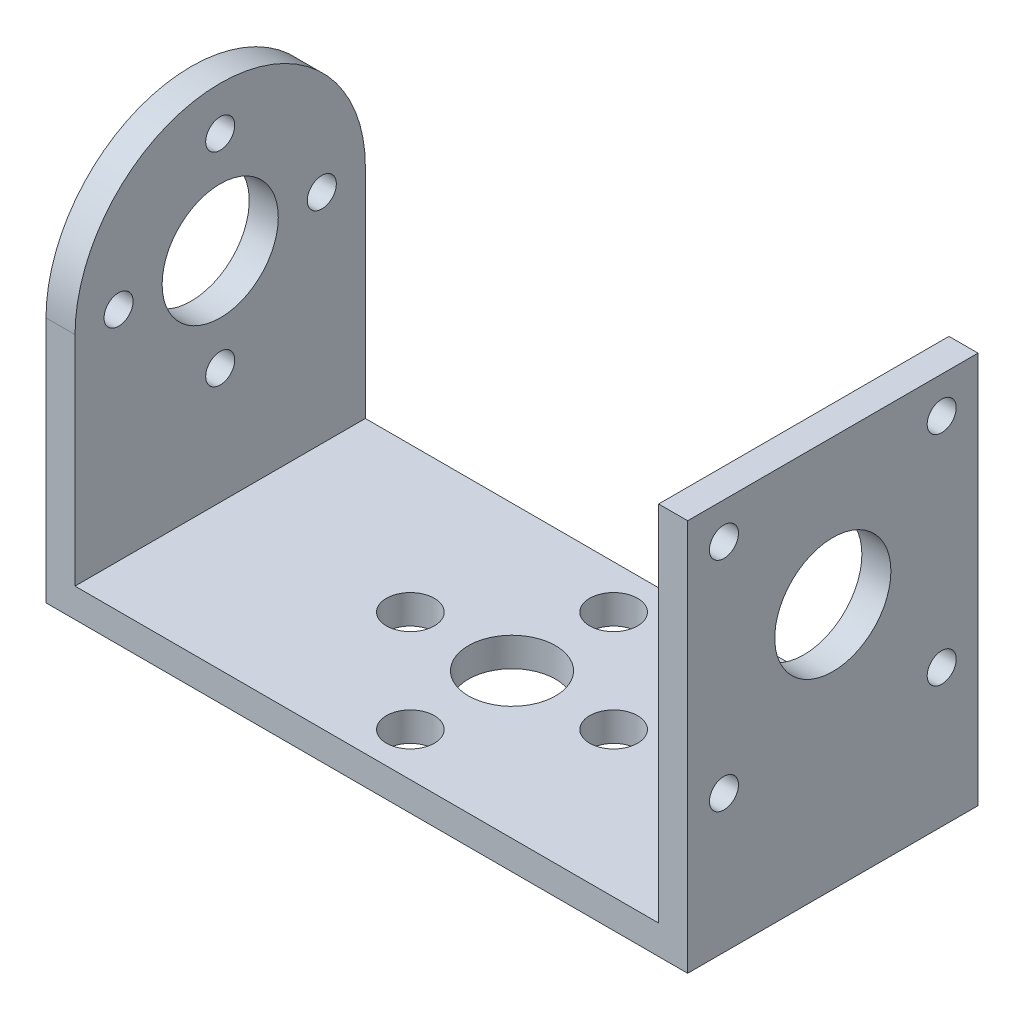
SolidWorks part; units mm, degrees
ref_plane "前视基准面" through (0, 0, 0) normal (0, 0, 1) x (1, 0, 0)
ref_plane "上视基准面" through (0, 0, 0) normal (0, 1, 0) x (1, 0, 0)
ref_plane "右视基准面" through (0, 0, 0) normal (1, 0, 0) x (0, 0, -1)
sketch "草图1" plane through (0, 0, 0) normal (0, 1, 0) x (1, 0, 0)
  line L1 (-22.1, -10) -> (22.1, -10)
  line L2 (-22.1, -10) -> (-22.1, 10)
  line L3 (-22.1, 10) -> (22.1, 10)
  line L4 (22.1, -10) -> (22.1, 10)
  line L5 (-22.1, -10) -> (22.1, 10) construction
  line L6 (-22.1, 10) -> (22.1, -10) construction
  point P0 (0, 0)
  dimension "D1" = 20
  dimension "D2" = 44.2
extrude "凸台-拉伸1" add sketch "草图1" along normal blind 2
sketch "草图2" plane through (0, 2, 0) normal (0, 1, 0) x (1, 0, 0)
  line L0 (0, 10) -> (0, -10) construction
  line L2 (0, 0) -> (7.7612, -7.7612) construction
  line L6 (-7, 0) -> (7, 0) construction
  circle A0 centre (0, 0) radius 3
  circle A1 centre (0, 0) radius 7 construction
  circle A2 centre (0, 7) radius 1.65
  circle A3 centre (7, 0) radius 1.65
  circle A4 centre (0, -7) radius 1.65
  circle A5 centre (-7, 0) radius 1.65
  arc A7 (-2.9294, -0.6468) -> (-2.9294, 0.6468) centre (-9.8995, 0) ccw construction
  point P20 (0, 0)
  dimension "D1" = 14
  dimension "D2" = 3.3
  dimension "D3" = 3.3
  dimension "D4" = 3.3
  dimension "D5" = 3.3
extrude "切除-拉伸1" cut sketch "草图2" against normal up to next
sketch "草图3" plane through (-22.1, 0, 0) normal (-1, 0, 0) x (0, 0, 1)
  line L1 (-10, 2) -> (10, 2)
  line L2 (-10, 2) -> (-10, 27)
  line L3 (-10, 27) -> (10, 27)
  line L4 (10, 2) -> (10, 27)
  dimension "D1" = 25
extrude "凸台-拉伸2" add sketch "草图3" against normal blind 2
ref_plane "基准面1" through (0, 0, 0) normal (-1, 0, 0) x (0, 0, 1)
mirror "镜向2" about plane through (0, 0, 0) normal (-1, 0, 0) of "凸台-拉伸2"
sketch "草图4" plane through (-22.1, 0, 0) normal (-1, 0, 0) x (0, 0, 1)
  line L0 (0, 27) -> (0, 0) construction
  line L1 (10, 27) -> (-10, 27) construction
  line L2 (10, 27) -> (10, 0) construction
  line L3 (-10, 27) -> (-10, 0) construction
  line L4 (10, 27) -> (10, 17)
  line L5 (10, 27) -> (-10, 27)
  line L6 (-10, 27) -> (-10, 17)
  arc A0 (10, 17) -> (-10, 17) centre (0, 17) ccw
  circle A1 centre (0, 17) radius 4
  circle A2 centre (0, 24) radius 1
  circle A3 centre (7, 17) radius 1
  circle A4 centre (0, 10) radius 1
  circle A5 centre (-7, 17) radius 1
  point P22 (0, 17)
  line M2 (10, 0) -> (10, 27)
  line M3 (10, 27) -> (-10, 27)
  line M4 (-10, 27) -> (-10, 0)
  dimension "D1" = 10
  dimension "D2" = 7
  dimension "D3" = 4
extrude "切除-拉伸2" cut sketch "草图4" against normal up to next contours A0 L5 M4 | A0 M2 M3 | L0 A4 | A4 L0 | A1 L0 | L0 A1 | A3 | A2 | A5
sketch "草图5" plane through (22.1, 0, 0) normal (1, 0, 0) x (0, 0, -1)
  line L0 (0, 27) -> (0, 0) construction
  line L1 (-10, 27) -> (10, 27) construction
  circle A0 centre (0, 17) radius 4
  circle A1 centre (-7.5, 24.5) radius 1
  circle A2 centre (7.5, 24.5) radius 1
  circle A3 centre (7.5, 9.5) radius 1
  circle A4 centre (-7.5, 9.5) radius 1
  dimension "D1" = 10
  dimension "D2" = 7.5
  dimension "D3" = 7.5
  dimension "D4" = 2
extrude "切除-拉伸3" cut sketch "草图5" against normal up to next
